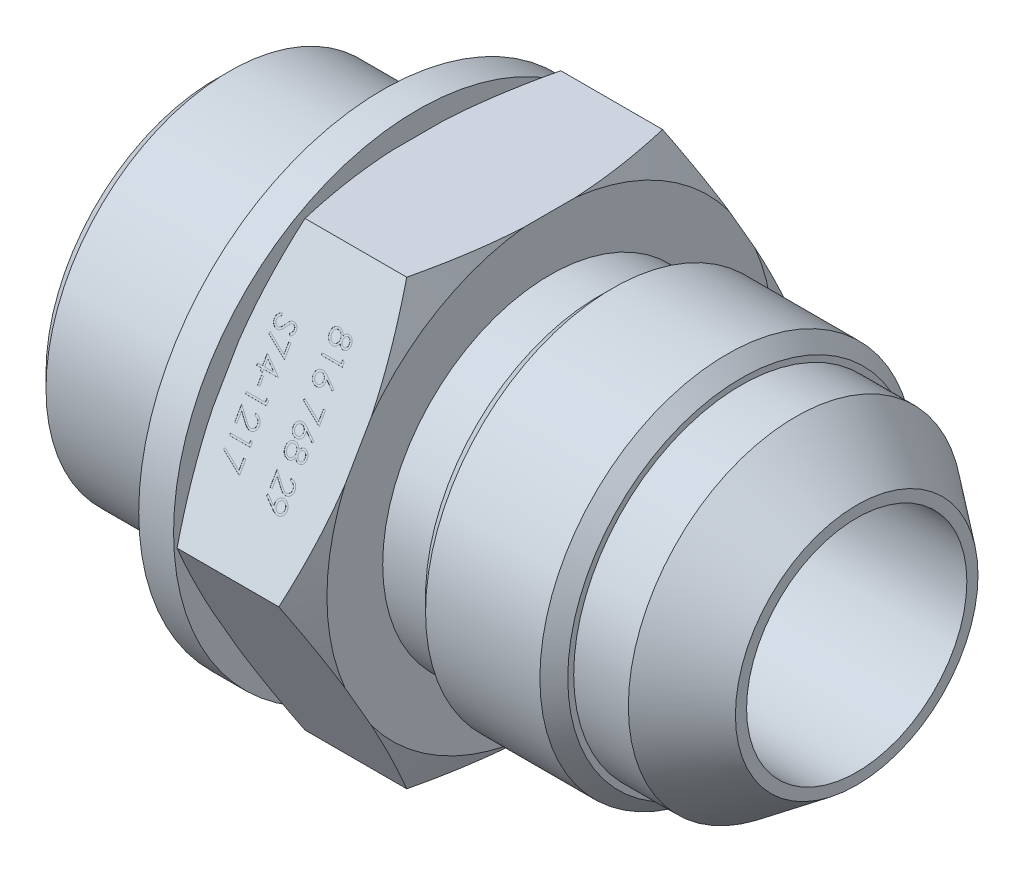
SolidWorks part; units mm, degrees
material "4140 H/T"
ref_plane "Front Plane" through (0, 0, 0) normal (0, 0, 1) x (1, 0, 0)
ref_plane "Top Plane" through (0, 0, 0) normal (0, 1, 0) x (1, 0, 0)
ref_plane "Right Plane" through (0, 0, 0) normal (1, 0, 0) x (0, 0, -1)
sketch "Sketch1" plane through (0, 0, 0) normal (0, 0, 1) x (1, 0, 0)
  line L0 (0, 0) -> (53.9967, 0) construction
  line L1 (0, 10.5) -> (0, 13.15)
  line L2 (11.4, 13.15) -> (12.5, 12.05)
  line L3 (0, 13.15) -> (11.4, 13.15)
  line L4 (14.5, 12.05) -> (14.5, 16)
  line L5 (15.6, 18.35) -> (22.9, 18.35)
  line L6 (24, 16) -> (24, 12)
  line L7 (24, 12) -> (27.5, 12)
  line L8 (27.5, 12) -> (27.5, 13.425)
  line L9 (27.5, 13.425) -> (37.7, 13.425)
  line L10 (37.7, 13.425) -> (37.7, 12)
  line L11 (37.7, 12) -> (41.6208, 12)
  line L12 (41.6208, 12) -> (46, 8.7)
  line L13 (46, 8.7) -> (46, 7.9)
  line L14 (46, 7.9) -> (13, 7.9)
  line L15 (0, 10.5) -> (4.5033, 7.9)
  line L18 (13, 7.9) -> (4.5033, 7.9)
  line L19 (12.5, 12.05) -> (14.5, 12.05)
  line L20 (15.6, 18.35) -> (14.5, 16)
  line L21 (22.9, 18.35) -> (24, 16)
  dimension "D2" = 15.8
  dimension "D3" = 24
  dimension "D4" = 17.4
  dimension "D5" = 8.3
  dimension "D6" = 26.85
  dimension "D7" = 46
  dimension "D8" = 14.5
  dimension "D9" = 22
  dimension "D10" = 3.5
  dimension "D11" = 26.3
  dimension "D12" = 2
  dimension "D13" = 36.7
  dimension "D14" = 32
  dimension "D15" = 1.1
  dimension "D16" = 1.1
  dimension "D17" = 37
  dimension "D18" = 24
  dimension "D19" = 24.1
  dimension "D20" = 45
  dimension "D21" = 21
  dimension "D22" = 30
revolve "Revolve1" add sketch "Sketch1" angle 360 about L0
cosmetic thread "Cosmetic Thread1" parameters "D2"=24.117
cosmetic thread "Cosmetic Thread2" parameters "D2"=24.5
sketch "Sketch2" plane through (24, 0, 0) normal (1, 0, 0) x (0, 0, -1)
  line L1 (9.175, 15.8916) -> (-9.175, 15.8916)
  line L2 (-9.175, 15.8916) -> (-18.35, 0)
  line L3 (-18.35, 0) -> (-9.175, -15.8916)
  line L4 (-9.175, -15.8916) -> (9.175, -15.8916)
  line L5 (9.175, -15.8916) -> (18.35, 0)
  line L6 (18.35, 0) -> (9.175, 15.8916)
  circle A0 centre (0, 0) radius 15.8916 construction
  circle A1 centre (0, 0) radius 18.35 construction
extrude "Extrude1" cut sketch "Sketch2" against normal up to surface (9.5 mm away) flip side to cut up to face at (14.5, 0, 12.05)
sketch "Sketch3" plane through (14.5, 0, 0) normal (-1, 0, 0) x (0, 0, 1)
  circle A0 centre (0, 0) radius 17.5
  circle A1 centre (0, 0) radius 14.5
  dimension "D1" = 35
  dimension "D2" = 29
extrude "Extrude2" add sketch "Sketch3" along normal blind 2.5
chamfer "Chamfer1" distance 1 angle 45 1 edges at (0, 0, 13.15)
chamfer "Chamfer2" distance 1 angle 45 2 edges at (37.7, 0, 13.425) (27.5, 0, 13.425)
sketch "Sketch4" plane through (0, 7.9458, 13.7625) normal (0, -0.5, -0.866) x (1, 0, 0)
  line L0 (19.6699, 8.8208) -> (19.6699, -8.8208) construction
  text T0 "816 768 29\r\nS74-1217" font "Century Gothic" height 1.5
extrude "Cut-Extrude1" cut sketch "Sketch4" along normal blind 0.01
sketch "Sketch5" plane through (0, 0, 0) normal (0, 0, 1) x (1, 0, 0)
  line L0 (14.5, -17.5) -> (14.5, 17.5) construction
  line L1 (0, 0) -> (24.564, 0) construction
  circle A0 centre (13, 13.4674) radius 1.5
  dimension "D1" = 3
  dimension "D2" = 26.9347
revolve "Revolve2" add sketch "Sketch5" angle 360 about L1
